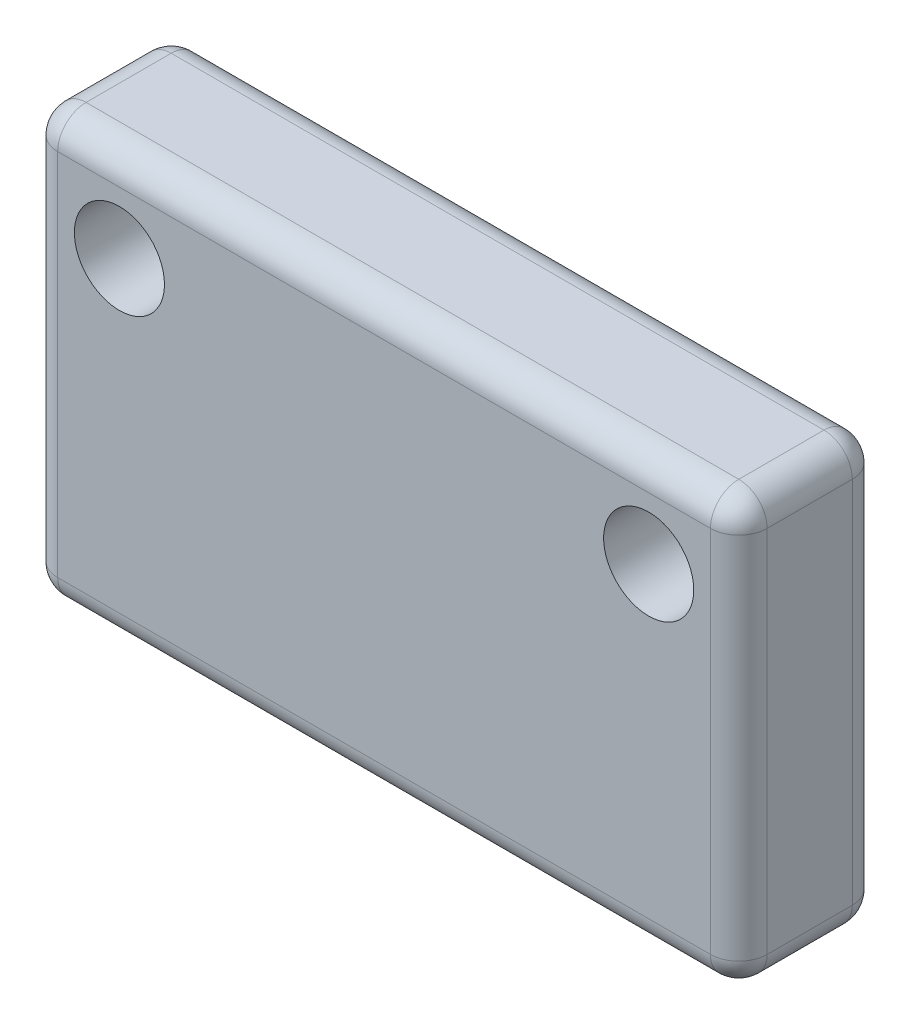
SolidWorks part; units mm, degrees
ref_plane "Plano frontal" through (0, 0, 0) normal (0, 0, 1) x (1, 0, 0)
ref_plane "Plano superior" through (0, 0, 0) normal (0, 1, 0) x (1, 0, 0)
ref_plane "Plano direito" through (0, 0, 0) normal (1, 0, 0) x (0, 0, -1)
sketch "Esboço1" plane through (0, 0, 0) normal (0, 0, 1) x (1, 0, 0)
  line L1 (12.5, -7.5) -> (-12.5, -7.5)
  line L2 (12.5, -7.5) -> (12.5, 7.5)
  line L3 (12.5, 7.5) -> (-12.5, 7.5)
  line L4 (-12.5, -7.5) -> (-12.5, 7.5)
  line L5 (12.5, -7.5) -> (-12.5, 7.5) construction
  line L6 (12.5, 7.5) -> (-12.5, -7.5) construction
  point P0 (0, 0)
  dimension "D1" = 25
  dimension "D2" = 15
extrude "Ressalto-extrusão1" add sketch "Esboço1" along normal blind 5
sketch "Esboço2" plane through (0, 0, 5) normal (0, 0, 1) x (1, 0, 0)
  line L1 (-12.5, 7.5) -> (-9.325, 7.5) construction
  line L2 (-12.5, 7.5) -> (-12.5, 4.325) construction
  line L3 (-12.5, 4.325) -> (-9.325, 4.325) construction
  line L4 (-12.5, 7.5) -> (-12.5, -7.5)
  line L5 (-12.5, -7.5) -> (12.5, -7.5)
  line L6 (12.5, -7.5) -> (12.5, 7.5)
  line L7 (12.5, 7.5) -> (-12.5, 7.5)
  line L8 (-12.5, 7.5) -> (-12.5, -7.5) construction
  line L9 (-12.5, -7.5) -> (12.5, -7.5)
  line L10 (12.5, -7.5) -> (12.5, 7.5) construction
  line L11 (12.5, 7.5) -> (-12.5, 7.5) construction
  line L12 (-9.325, 7.5) -> (-9.325, 4.325) construction
  line L13 (12.5, 7.5) -> (9.325, 7.5) construction
  line L14 (12.5, 7.5) -> (12.5, 4.325) construction
  line L15 (12.5, 4.325) -> (9.325, 4.325) construction
  line L16 (9.325, 7.5) -> (9.325, 4.325) construction
  circle A0 centre (-9.325, 4.325) radius 1.5875
  circle A1 centre (9.325, 4.325) radius 1.5875
  dimension "D3" = 3.175
  dimension "D2" = 3.175
  dimension "D1" = 0
extrude "Corte-extrusão1" cut sketch "Esboço2" against normal through all contours A0 | A1
fillet "Filete2" radius 1 12 edges at (0, -7.5, 0) (12.5, 0, 0) (-12.5, 0, 5) (0, -7.5, 5) (12.5, 0, 5) (0, 7.5, 5) (12.5, 7.5, 2.5) (12.5, -7.5, 2.5) (-12.5, -7.5, 2.5) (-12.5, 7.5, 2.5) (-12.5, 0, 0) (0, 7.5, 0)
